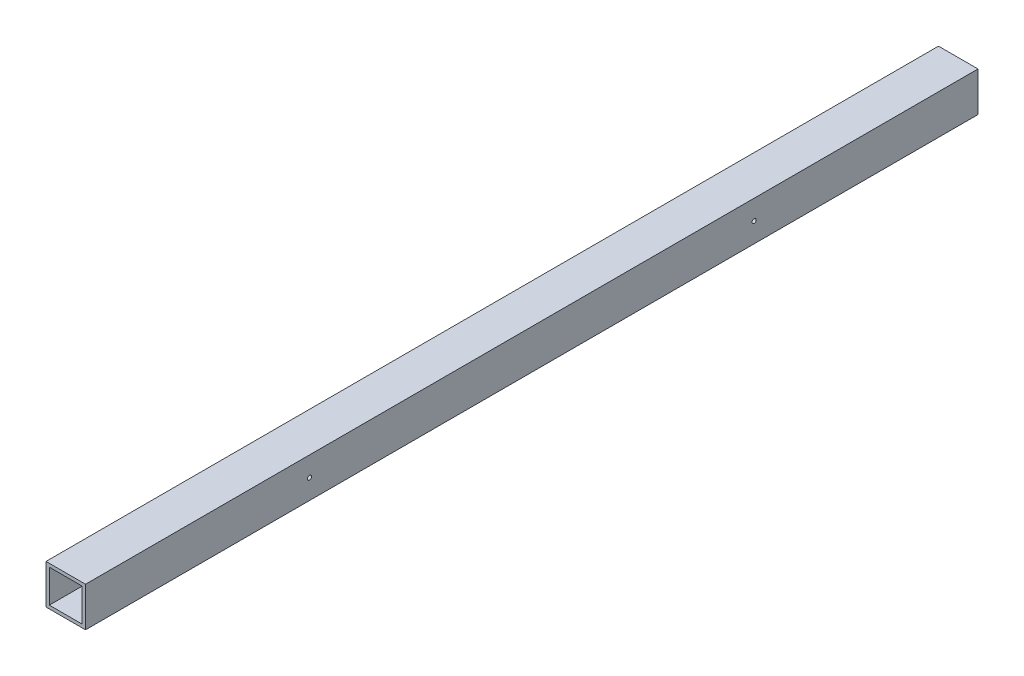
SolidWorks part; units mm, degrees
ref_plane "前视基准面" through (0, 0, 0) normal (0, 0, 1) x (1, 0, 0)
ref_plane "上视基准面" through (0, 0, 0) normal (0, 1, 0) x (1, 0, 0)
ref_plane "右视基准面" through (0, 0, 0) normal (1, 0, 0) x (0, 0, -1)
sketch "草图1" plane through (0, 0, 0) normal (0, 0, 1) x (1, 0, 0)
  line L0 (-12, 12) -> (12, 12)
  line L1 (-10, 10) -> (10, 10)
  line L2 (-10, 10) -> (-10, -10)
  line L3 (-10, -10) -> (10, -10)
  line L4 (10, 10) -> (10, -10)
  line L5 (-10, 10) -> (10, -10) construction
  line L6 (-10, -10) -> (10, 10) construction
  line L7 (12, 12) -> (12, -12)
  line L8 (-12, -12) -> (12, -12)
  line L9 (-12, 12) -> (-12, -12)
  point P0 (0, 0)
  dimension "D1" = 20
  dimension "D2" = 20
  dimension "D3" = 2
extrude "凸台-拉伸1" add sketch "草图1" along normal mid plane 542
sketch "草图2" plane through (-12, 0, 0) normal (-1, 0, 0) x (0, 0, 1)
  line L0 (-271, 12) -> (-271, -12) construction
  line L1 (0, 12) -> (0, -80.4026) construction
  line L2 (271, 12) -> (-271, 12) construction
  circle A0 centre (-259, 0) radius 3 construction
  circle A1 centre (-135, 0) radius 2 construction
  dimension "D1" = 12
  dimension "D2" = 136
hole_wizard "M3 螺纹孔的螺纹孔钻头3" positions "3D草图2" profile "草图9" hole size "M3" standard "GB" end condition through all
sketch3d "3D草图2"
  point P0 (-12, 0, -135)
sketch "草图9" plane through (-12, 0, -135) normal (0, 1, 0) x (0, 0, 1)
  line L0 (0, 0) -> (0, 24)
  line L1 (0, 24) -> (1.25, 24)
  line L2 (1.25, 24) -> (1.25, 0)
  line L5 (1.25, 0) -> (0, 0)
  line L11 (0, -6.35) -> (0, 107.95) construction
  dimension "通孔孔直径" = 2.5
  dimension "通孔孔深度" = 24
mirror "镜向1" about plane through (0, 0, 0) normal (0, 0, 1) of "M3 螺纹孔的螺纹孔钻头3"
